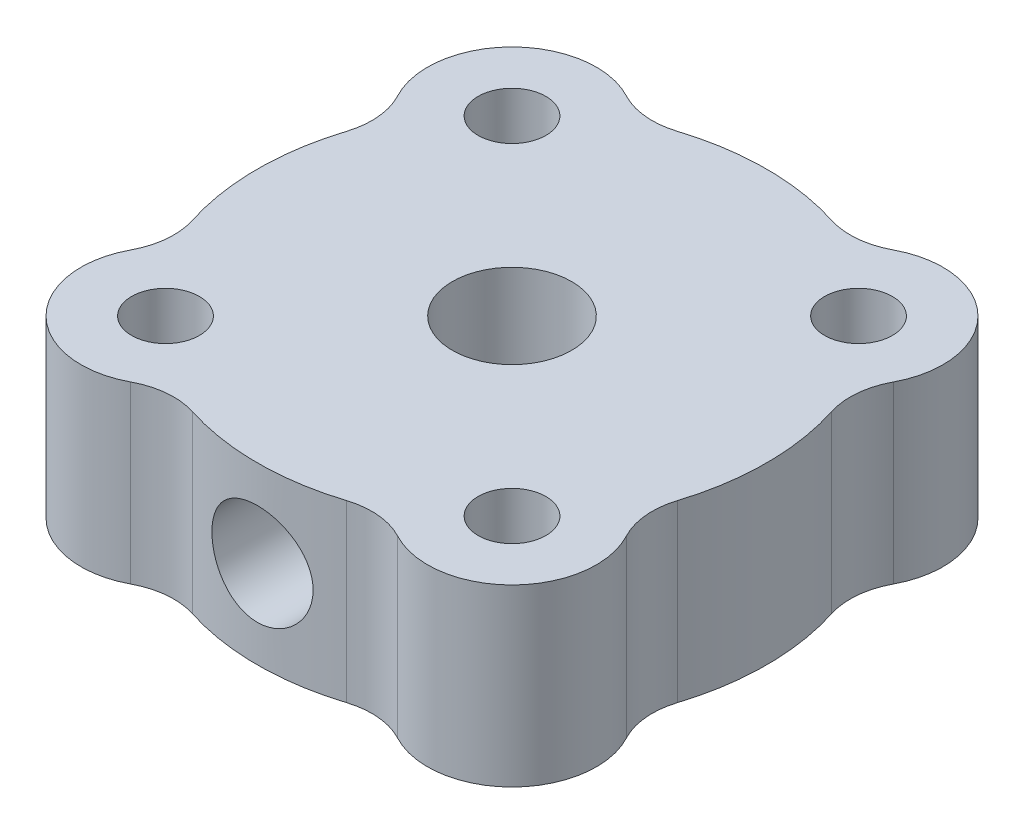
SolidWorks part; units mm, degrees
ref_plane "Front Plane" through (0, 0, 0) normal (0, 0, 1) x (1, 0, 0)
ref_plane "Top Plane" through (0, 0, 0) normal (0, 1, 0) x (1, 0, 0)
ref_plane "Right Plane" through (0, 0, 0) normal (1, 0, 0) x (0, 0, -1)
ref_plane "Plane1" through (0, 2.54, 0) normal (0, -1, 0) x (1, 0, 0)
sketch "Sketch1" plane through (0, 2.54, 0) normal (0, -1, 0) x (1, 0, 0)
  arc A0 (-4.3977, 9.1589) -> (-9.1589, 4.3977) centre (-6.9148, 6.9148) ccw
  arc A1 (-9.1589, 4.3977) -> (-4.3977, 9.1589) centre (0, 0) ccw
extrude "Boss-Extrude1" add sketch "Sketch1" against normal blind 6.985
sketch "Sketch2" plane through (0, 2.54, 0) normal (0, -1, 0) x (1, 0, 0)
  arc A0 (-9.1589, -4.3977) -> (-4.3977, -9.1589) centre (-6.9148, -6.9148) ccw
  arc A1 (-4.3977, -9.1589) -> (-9.1589, -4.3977) centre (0, 0) cw
extrude "Boss-Extrude2" add sketch "Sketch2" against normal blind 6.985
sketch "Sketch3" plane through (0, 2.54, 0) normal (0, -1, 0) x (1, 0, 0)
  arc A0 (4.3977, -9.1589) -> (9.1589, -4.3977) centre (6.9148, -6.9148) ccw
  arc A1 (9.1589, -4.3977) -> (4.3977, -9.1589) centre (0, 0) cw
extrude "Boss-Extrude3" add sketch "Sketch3" against normal blind 6.985
ref_plane "Plane2" through (0, 9.525, 0) normal (0, 1, 0) x (1, 0, 0)
sketch "Sketch4" plane through (0, 9.525, 0) normal (0, 1, 0) x (1, 0, 0)
  arc A0 (9.1589, -4.3977) -> (4.3977, -9.1589) centre (0, 0) cw
  arc A1 (4.3977, -9.1589) -> (9.1589, -4.3977) centre (6.9148, -6.9148) ccw
extrude "Boss-Extrude4" add sketch "Sketch4" against normal blind 6.985
sketch "Sketch5" plane through (0, 0, 0) normal (0, 0, 1) x (1, 0, 0)
  line L0 (6.35, 2.54) -> (0, 2.54)
  line L1 (0, 2.54) -> (0, 0)
  line L2 (0, 0) -> (6.35, 0)
  line L3 (6.35, 0) -> (6.35, 2.54)
  line L4 (0, 2.54) -> (0, 0) construction
revolve "Revolve1" add sketch "Sketch5" angle 360 about L4
hole_wizard "M2.5 Clearance Hole1" positions "Sketch7" profile "Sketch6" hole size "M2.5" standard "ANSI Metric"
sketch "Sketch7" plane through (0, 2.54, 0) normal (0, -1, 0) x (-1, 0, 0)
  point P0 (-6.9148, 6.9148)
  point P1 (-6.9148, -6.9148)
  point P2 (6.9148, -6.9148)
  point P3 (6.9148, 6.9148)
sketch "Sketch6" plane through (6.9148, 2.54, -6.9148) normal (1, 0, 0) x (0, 0, -1)
  line L0 (0, 0) -> (0, 6.985)
  line L1 (0, 6.985) -> (1.3525, 6.985)
  line L2 (1.3525, 6.985) -> (1.3525, 0)
  line L5 (1.3525, 0) -> (0, 0)
  line L11 (0, -6.35) -> (0, 107.95) construction
  dimension "Thru Hole Dia." = 2.7051
  dimension "Thru Hole Depth" = 6.985
hole_wizard "M4 Clearance Hole1" positions "Sketch9" profile "Sketch8" hole size "M4" standard "ANSI Metric"
sketch "Sketch9" plane through (0, 0, 0) normal (0, -1, 0) x (-1, 0, 0)
  point P0 (0, 0)
sketch "Sketch8" plane through (0, 0, 0) normal (1, 0, 0) x (0, 0, -1)
  line L0 (0, 0) -> (0, 9.525)
  line L1 (0, 9.525) -> (2.3812, 9.525)
  line L2 (2.3812, 9.525) -> (2.3812, 0)
  line L5 (2.3812, 0) -> (0, 0)
  line L11 (0, -6.35) -> (0, 107.95) construction
  dimension "Thru Hole Dia." = 4.7625
  dimension "Thru Hole Depth" = 9.525
hole_wizard "M3.5 Clearance Hole1" positions "3DSketch1" profile "Sketch10" hole size "M3.5" standard "ANSI Metric"
sketch3d "3DSketch1"
  point P0 (0, 6.0325, 10.16)
sketch "Sketch10" plane through (0, 6.0325, 10.16) normal (1, 0, 0) x (0, -1, 0)
  line L0 (0, 0) -> (0, 7.7788)
  line L1 (0, 7.7788) -> (2.0193, 7.7788)
  line L2 (2.0193, 7.7788) -> (2.0193, 0)
  line L5 (2.0193, 0) -> (0, 0)
  line L11 (0, -6.35) -> (0, 107.95) construction
  dimension "Thru Hole Dia." = 4.0386
  dimension "Thru Hole Depth" = 7.7788
fillet "Fillet1" radius 2.921 8 edges at (4.3977, 6.0325, -9.1589) (9.1589, 6.0325, -4.3977) (4.3977, 6.0325, 9.1589) (9.1589, 6.0325, 4.3977) (-4.3977, 6.0325, 9.1589) (-9.1589, 6.0325, 4.3977) (-9.1589, 6.0325, -4.3977) (-4.3977, 6.0325, -9.1589)
